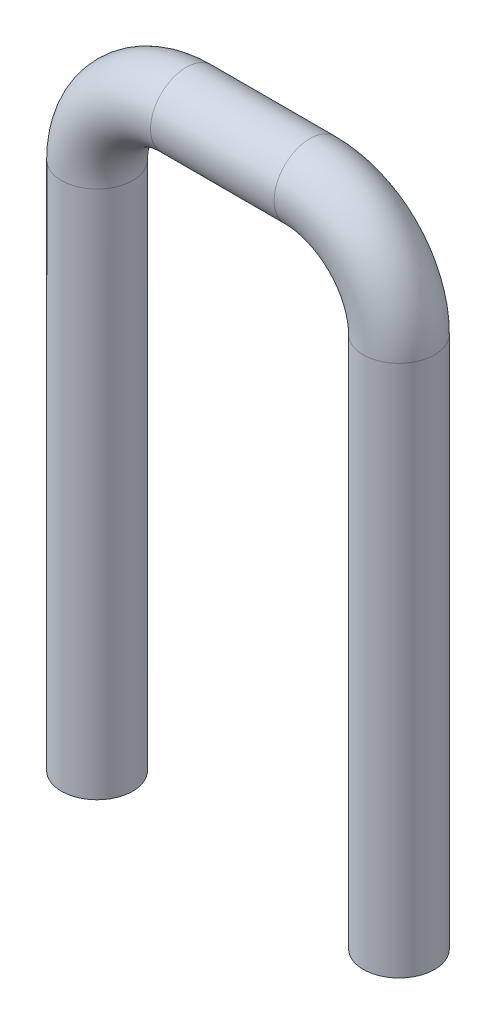
SolidWorks part; units mm, degrees
ref_plane "Front Plane" through (0, 0, 0) normal (0, 0, 1) x (1, 0, 0)
ref_plane "Top Plane" through (0, 0, 0) normal (0, 1, 0) x (1, 0, 0)
ref_plane "Right Plane" through (0, 0, 0) normal (1, 0, 0) x (0, 0, -1)
sketch "Sketch1" plane through (0, 0, 0) normal (0, 0, 1) x (1, 0, 0)
  line L0 (0, 0) -> (0, 1.85)
  line L1 (0.75, 2.6) -> (1.79, 2.6)
  line L2 (2.54, 1.85) -> (2.54, -0.0285)
  line L3 (1.79, 1.85) -> (1.79, 2.6) construction
  line L4 (0.75, 1.85) -> (0, 1.85) construction
  arc A0 (0, 1.85) -> (0.75, 2.6) centre (0.75, 1.85) cw
  arc A1 (1.79, 2.6) -> (2.54, 1.85) centre (1.79, 1.85) cw
  dimension "D3" = 0.75
  dimension "D4" = 0.75
  dimension "D1" = 2.54
  dimension "D2" = 2.6
sketch "Sketch2" plane through (0, 0, 0) normal (0, 1, 0) x (1, 0, 0)
  circle A0 centre (0, 0) radius 0.3
  dimension "D1" = 0.6
sweep "Sweep1" add profiles "Sketch2" path "Sketch1"
sketch "Sketch4" plane through (0, 0, 0) normal (0, -1, 0) x (1, 0, 0)
  circle A0 centre (0, 0) radius 0.3
extrude "Boss-Extrude1" add sketch "Sketch4" along normal blind 2.6
sketch "Sketch5" plane through (0, -0.0285, 0) normal (0, -1, 0) x (1, 0, 0)
  circle A1 centre (2.54, 0) radius 0.3
  circle A2 centre (2.54, 0) radius 0.3
  dimension "D1" = 0
extrude "Boss-Extrude2" add sketch "Sketch5" along normal blind 2.6
